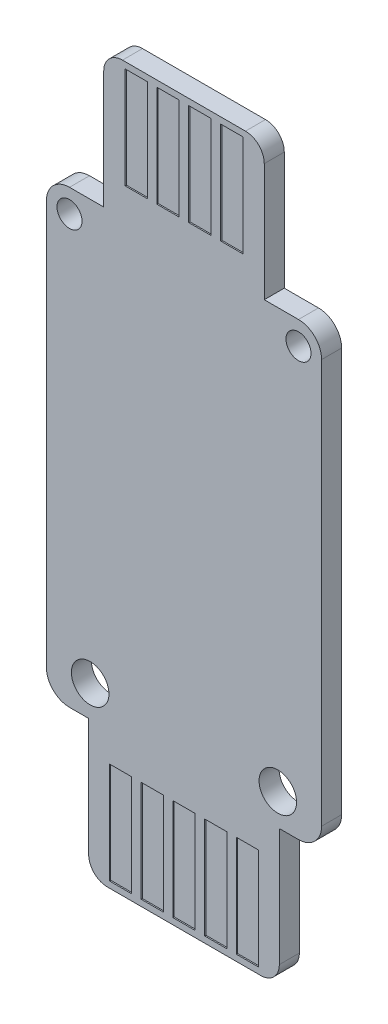
SolidWorks part; units mm, degrees
ref_plane "前视基准面" through (0, 0, 0) normal (0, 0, 1) x (1, 0, 0)
ref_plane "上视基准面" through (0, 0, 0) normal (0, 1, 0) x (1, 0, 0)
ref_plane "右视基准面" through (0, 0, 0) normal (1, 0, 0) x (0, 0, -1)
other "Configuration Table"
sketch "草图1" plane through (0, 0, 0) normal (0, 0, 1) x (1, 0, 0)
  line L1 (-9.15, 16) -> (9.15, 16)
  line L2 (-11, 14.15) -> (-11, -20)
  line L3 (-11, -20) -> (11, -20)
  line L4 (11, 14.15) -> (11, -20)
  arc A0 (-9.15, 16) -> (-11, 14.15) centre (-9.15, 14.15) ccw
  circle A1 centre (-9.15, 14.15) radius 1
  arc A2 (11, 14.15) -> (9.15, 16) centre (9.15, 14.15) ccw
  circle A3 centre (9.15, 14.15) radius 1
  point P0 (0, 0)
  point P6 (0, 0)
  dimension "D5" = 3.7
  dimension "D6" = 2
  dimension "D3" = 3.7
  dimension "D4" = 2
  dimension "D1" = 20
  dimension "D2" = 22
  dimension "D7" = 11
  dimension "D8" = 36
extrude "凸台-拉伸1" add sketch "草图1" along normal blind 1.6
sketch "草图3" plane through (0, 0, 0) normal (0, 0, 1) x (1, 0, 0)
  line L0 (-11, -20) -> (11, -20) construction
  line L1 (-10, -20) -> (10, -20) construction
  line L2 (-10, -20) -> (-10, 12) construction
  line L3 (-10, 12) -> (10, 12) construction
  line L4 (10, -20) -> (10, 12) construction
  line L5 (-11, 14.15) -> (-11, -20) construction
  circle A0 centre (-7.5, -17.5) radius 1.5
  circle A1 centre (7.5, -17.5) radius 1.5
  dimension "D4" = 3
  dimension "D7" = 3
  dimension "D1" = 32
  dimension "D2" = 20
  dimension "D3" = 1
  dimension "D5" = 2.5
  dimension "D6" = 2.5
  dimension "D8" = 2.5
  dimension "D9" = 2.5
extrude "切除-拉伸1" cut sketch "草图3" along normal blind 1.6
sketch "草图5" plane through (0, 0, 0) normal (0, 0, 1) x (1, 0, 0)
  line L0 (11, -20) -> (11, 14.15) construction
  line L1 (-11, -20) -> (11, -20) construction
  line L2 (-11, 14.15) -> (-11, -20) construction
  line L3 (11, -20) -> (11, -18.15)
  line L4 (-11, -20) -> (-9.15, -20)
  line L5 (-11, -18.15) -> (-11, -20)
  line L6 (9.15, -20) -> (11, -20)
  arc A0 (-11, -18.15) -> (-9.15, -20) centre (-9.15, -18.15) ccw
  arc A1 (9.15, -20) -> (11, -18.15) centre (9.15, -18.15) ccw
  dimension "D1" = 3.7
  dimension "D2" = 3.7
extrude "切除-拉伸2" cut sketch "草图5" along normal up to surface (1.6 mm away) up to face at (-6, -17.5, 1.6)
sketch "草图7" plane through (0, 0, 0) normal (0, 0, 1) x (1, 0, 0)
  line L0 (9.15, 16) -> (-9.15, 16) construction
  line L1 (-4.915, 26.92) -> (4.915, 26.92)
  line L2 (-6.415, 25.42) -> (-6.415, 16)
  line L3 (-6.415, 16) -> (6.415, 16)
  line L4 (6.415, 25.42) -> (6.415, 16)
  line L5 (-9.15, -20) -> (9.15, -20) construction
  line L6 (-6.415, -20) -> (6.415, -20)
  line L7 (-6.415, -20) -> (-6.415, -29.42)
  line L8 (-4.915, -30.92) -> (4.915, -30.92)
  line L9 (6.415, -20) -> (6.415, -29.42)
  arc A0 (-4.915, 26.92) -> (-6.415, 25.42) centre (-4.915, 25.42) ccw
  arc A1 (6.415, 25.42) -> (4.915, 26.92) centre (4.915, 25.42) ccw
  arc A2 (-6.415, -29.42) -> (-4.915, -30.92) centre (-4.915, -29.42) ccw
  arc A3 (4.915, -30.92) -> (6.415, -29.42) centre (4.915, -29.42) ccw
  point P6 (0, 16)
  point P7 (0, 16)
  point P19 (0, -20)
  point P20 (0, -20)
  dimension "D3" = 3
  dimension "D4" = 3
  dimension "D7" = 3
  dimension "D8" = 3
  dimension "D1" = 12.83
  dimension "D2" = 10.92
  dimension "D5" = 10.92
  dimension "D6" = 12.83
extrude "凸台-拉伸2" add sketch "草图7" along normal up to surface (1.6 mm away) up to face at (-6, -17.5, 1.6)
sketch "草图8" plane through (0, 0, 0) normal (0, 0, 1) x (1, 0, 0)
  line L0 (4.915, 26.92) -> (-4.915, 26.92) construction
  line L1 (-2.16, 26.42) -> (-0.38, 26.42)
  line L2 (-2.16, 26.42) -> (-2.16, 18.32)
  line L3 (-2.16, 18.32) -> (-0.38, 18.32)
  line L4 (-0.38, 26.42) -> (-0.38, 18.32)
  line L5 (0, -1000) -> (0, 49000) construction
  line L6 (0, -30.92) -> (0, 26.92) construction
  line L7 (-4.915, -30.92) -> (4.915, -30.92) construction
  line L8 (-1000, -2) -> (49000, -2) construction
  line L9 (-4.7, 26.42) -> (-2.92, 26.42)
  line L10 (-4.7, 26.42) -> (-4.7, 18.32)
  line L11 (-4.7, 18.32) -> (-2.92, 18.32)
  line L12 (-2.92, 26.42) -> (-2.92, 18.32)
  line L13 (-2.16, 26.42) -> (-4.7, 26.42) construction
  line L14 (2.16, 26.42) -> (4.7, 26.42) construction
  line L15 (2.92, 26.42) -> (2.92, 18.32)
  line L16 (4.7, 18.32) -> (2.92, 18.32)
  line L17 (4.7, 26.42) -> (4.7, 18.32)
  line L18 (4.7, 26.42) -> (2.92, 26.42)
  line L19 (0.38, 26.42) -> (0.38, 18.32)
  line L20 (2.16, 18.32) -> (0.38, 18.32)
  line L21 (2.16, 26.42) -> (2.16, 18.32)
  line L22 (2.16, 26.42) -> (0.38, 26.42)
  line L23 (2.16, -30.42) -> (4.7, -30.42) construction
  line L24 (-2.16, -30.42) -> (-4.7, -30.42) construction
  line L25 (0, 996) -> (0, -49004) construction
  line L26 (2.16, -30.42) -> (0.38, -30.42)
  line L27 (2.16, -30.42) -> (2.16, -22.32)
  line L28 (2.16, -22.32) -> (0.38, -22.32)
  line L29 (0.38, -30.42) -> (0.38, -22.32)
  line L30 (4.7, -30.42) -> (2.92, -30.42)
  line L31 (4.7, -30.42) -> (4.7, -22.32)
  line L32 (4.7, -22.32) -> (2.92, -22.32)
  line L33 (2.92, -30.42) -> (2.92, -22.32)
  line L34 (-2.92, -30.42) -> (-2.92, -22.32)
  line L35 (-4.7, -22.32) -> (-2.92, -22.32)
  line L36 (-4.7, -30.42) -> (-4.7, -22.32)
  line L37 (-4.7, -30.42) -> (-2.92, -30.42)
  line L38 (-0.38, -30.42) -> (-0.38, -22.32)
  line L39 (-2.16, -22.32) -> (-0.38, -22.32)
  line L40 (-2.16, -30.42) -> (-2.16, -22.32)
  line L41 (-2.16, -30.42) -> (-0.38, -30.42)
  point P16 (0, -2)
  dimension "D1" = 1.78
  dimension "D2" = 8.1
  dimension "D3" = 0.5
  dimension "D4" = 0.38
  dimension "D5" = 2
  dimension "D6" = 2.54
extrude "切除-拉伸3" cut sketch "草图8" along normal blind 0.1
sketch "草图9" plane through (0, 0, 0) normal (0, 0, 1) x (1, 0, 0)
  line L4 (-0.38, 26.42) -> (-2.16, 26.42)
  line L5 (-0.38, 18.32) -> (-0.38, 26.42)
  line L6 (-2.16, 18.32) -> (-0.38, 18.32)
  line L7 (-2.16, 26.42) -> (-2.16, 18.32)
  line L8 (-0.38, 26.42) -> (-2.16, 26.42)
  line L9 (-0.38, 18.32) -> (-0.38, 26.42)
  line L10 (-2.16, 18.32) -> (-0.38, 18.32)
  line L11 (-2.16, 26.42) -> (-2.16, 18.32)
  line L12 (0.38, 26.42) -> (0.38, 18.32)
  line L13 (0.38, 18.32) -> (2.16, 18.32)
  line L14 (2.16, 18.32) -> (2.16, 26.42)
  line L15 (2.16, 26.42) -> (0.38, 26.42)
  line L16 (0.38, 26.42) -> (0.38, 18.32)
  line L17 (0.38, 18.32) -> (2.16, 18.32)
  line L18 (2.16, 18.32) -> (2.16, 26.42)
  line L19 (2.16, 26.42) -> (0.38, 26.42)
  line L20 (2.92, 26.42) -> (2.92, 18.32)
  line L21 (2.92, 18.32) -> (4.7, 18.32)
  line L22 (4.7, 18.32) -> (4.7, 26.42)
  line L23 (4.7, 26.42) -> (2.92, 26.42)
  line L24 (2.92, 26.42) -> (2.92, 18.32)
  line L25 (2.92, 18.32) -> (4.7, 18.32)
  line L26 (4.7, 18.32) -> (4.7, 26.42)
  line L27 (4.7, 26.42) -> (2.92, 26.42)
  line L28 (-2.92, 26.42) -> (-4.7, 26.42)
  line L29 (-2.92, 18.32) -> (-2.92, 26.42)
  line L30 (-4.7, 18.32) -> (-2.92, 18.32)
  line L31 (-4.7, 26.42) -> (-4.7, 18.32)
  line L32 (-2.92, 26.42) -> (-4.7, 26.42)
  line L33 (-2.92, 18.32) -> (-2.92, 26.42)
  line L34 (-4.7, 18.32) -> (-2.92, 18.32)
  line L35 (-4.7, 26.42) -> (-4.7, 18.32)
  line L36 (-0.38, -30.42) -> (-0.38, -22.32)
  line L37 (-0.38, -22.32) -> (-2.16, -22.32)
  line L38 (-2.16, -22.32) -> (-2.16, -30.42)
  line L39 (-2.16, -30.42) -> (-0.38, -30.42)
  line L40 (-0.38, -30.42) -> (-0.38, -22.32)
  line L41 (-0.38, -22.32) -> (-2.16, -22.32)
  line L42 (-2.16, -22.32) -> (-2.16, -30.42)
  line L43 (-2.16, -30.42) -> (-0.38, -30.42)
  line L44 (-2.92, -30.42) -> (-2.92, -22.32)
  line L45 (-2.92, -22.32) -> (-4.7, -22.32)
  line L46 (-4.7, -22.32) -> (-4.7, -30.42)
  line L47 (-4.7, -30.42) -> (-2.92, -30.42)
  line L48 (-2.92, -30.42) -> (-2.92, -22.32)
  line L49 (-2.92, -22.32) -> (-4.7, -22.32)
  line L50 (-4.7, -22.32) -> (-4.7, -30.42)
  line L51 (-4.7, -30.42) -> (-2.92, -30.42)
  line L52 (2.92, -30.42) -> (4.7, -30.42)
  line L53 (4.7, -30.42) -> (4.7, -22.32)
  line L54 (4.7, -22.32) -> (2.92, -22.32)
  line L55 (2.92, -22.32) -> (2.92, -30.42)
  line L56 (2.92, -30.42) -> (4.7, -30.42)
  line L57 (4.7, -30.42) -> (4.7, -22.32)
  line L58 (4.7, -22.32) -> (2.92, -22.32)
  line L59 (2.92, -22.32) -> (2.92, -30.42)
  line L60 (0.38, -30.42) -> (2.16, -30.42)
  line L61 (2.16, -30.42) -> (2.16, -22.32)
  line L62 (2.16, -22.32) -> (0.38, -22.32)
  line L63 (0.38, -22.32) -> (0.38, -30.42)
  line L64 (0.38, -30.42) -> (2.16, -30.42)
  line L65 (2.16, -30.42) -> (2.16, -22.32)
  line L66 (2.16, -22.32) -> (0.38, -22.32)
  line L67 (0.38, -22.32) -> (0.38, -30.42)
  dimension "D1" = 0
  dimension "D2" = 0
  dimension "D3" = 0
  dimension "D4" = 0
  dimension "D5" = 0
  dimension "D6" = 0
  dimension "D7" = 0
  dimension "D8" = 0
extrude "切除-拉伸4" cut sketch "草图9" against normal blind 0.1 from surface at 1.6 starting at face at (-6, -17.5, 1.6)
sketch "草图11" plane through (0, 0, 0) normal (0, 0, 1) x (1, 0, 0)
  line L0 (6.415, -20) -> (9.15, -20) construction
  line L1 (-7.62, -20) -> (7.62, -20)
  line L2 (-7.62, -20) -> (-7.62, -29.42)
  line L3 (-6.12, -30.92) -> (6.12, -30.92)
  line L4 (7.62, -20) -> (7.62, -29.42)
  line L5 (-4.915, -30.92) -> (4.915, -30.92) construction
  arc A0 (-7.62, -29.42) -> (-6.12, -30.92) centre (-6.12, -29.42) ccw
  arc A1 (6.12, -30.92) -> (7.62, -29.42) centre (6.12, -29.42) ccw
  point P8 (0, -20)
  dimension "D4" = 3
  dimension "D5" = 3
  dimension "D1" = 0
  dimension "D2" = 0
  dimension "D3" = 15.24
extrude "凸台-拉伸3" add sketch "草图11" along normal up to surface (1.6 mm away) from surface at 0 up to face at (-6, -17.5, 1.6) starting at face at (3.81, 22.37, 0)
sketch "草图12" plane through (0, 0, 0) normal (0, 0, 1) x (1, 0, 0)
  line L0 (1.65, -22.32) -> (1.65, -30.42)
  line L1 (1.65, -22.32) -> (3.43, -22.32)
  line L2 (-6.12, -30.92) -> (6.12, -30.92) construction
  line L3 (-0.89, -22.32) -> (0.89, -22.32)
  line L4 (-0.89, -22.32) -> (-0.89, -30.42)
  line L5 (-0.89, -30.42) -> (0.89, -30.42)
  line L6 (0.89, -22.32) -> (0.89, -30.42)
  line L7 (3.43, -22.32) -> (3.43, -30.42)
  line L8 (1.65, -30.42) -> (3.43, -30.42)
  line L9 (4.19, -22.32) -> (4.19, -30.42)
  line L10 (4.19, -22.32) -> (5.97, -22.32)
  line L11 (5.97, -22.32) -> (5.97, -30.42)
  line L12 (4.19, -30.42) -> (5.97, -30.42)
  line L13 (-0.89, -22.32) -> (1.65, -22.32) construction
  line L14 (-3.43, -22.32) -> (-1.65, -22.32)
  line L15 (-3.43, -22.32) -> (-3.43, -30.42)
  line L16 (-3.43, -30.42) -> (-1.65, -30.42)
  line L17 (-1.65, -22.32) -> (-1.65, -30.42)
  line L18 (-5.97, -22.32) -> (-4.19, -22.32)
  line L19 (-5.97, -22.32) -> (-5.97, -30.42)
  line L20 (-5.97, -30.42) -> (-4.19, -30.42)
  line L21 (-4.19, -22.32) -> (-4.19, -30.42)
  line L22 (-0.89, -22.32) -> (-3.43, -22.32) construction
  point P2 (0, -22.32)
  dimension "D1" = 8.1
  dimension "D2" = 1.78
  dimension "D3" = 0.5
  dimension "D5" = 2.54
  dimension "D7" = 2.54
  dimension "D4" = 3
  dimension "D6" = 3
extrude "切除-拉伸5" cut sketch "草图12" along normal blind 0.1 from surface at 0 starting at face at (3.81, 22.37, 0)
sketch "草图13" plane through (0, 0, 0) normal (0, 0, 1) x (1, 0, 0)
  line L4 (0.89, -22.32) -> (-0.89, -22.32)
  line L5 (0.89, -30.42) -> (0.89, -22.32)
  line L6 (-0.89, -30.42) -> (0.89, -30.42)
  line L7 (-0.89, -22.32) -> (-0.89, -30.42)
  line L8 (0.89, -22.32) -> (-0.89, -22.32)
  line L9 (0.89, -30.42) -> (0.89, -22.32)
  line L10 (-0.89, -30.42) -> (0.89, -30.42)
  line L11 (-0.89, -22.32) -> (-0.89, -30.42)
  line L12 (1.65, -22.32) -> (1.65, -30.42)
  line L13 (1.65, -30.42) -> (3.43, -30.42)
  line L14 (3.43, -30.42) -> (3.43, -22.32)
  line L15 (3.43, -22.32) -> (1.65, -22.32)
  line L16 (1.65, -22.32) -> (1.65, -30.42)
  line L17 (1.65, -30.42) -> (3.43, -30.42)
  line L18 (3.43, -30.42) -> (3.43, -22.32)
  line L19 (3.43, -22.32) -> (1.65, -22.32)
  line L20 (-4.19, -22.32) -> (-5.97, -22.32)
  line L21 (-4.19, -30.42) -> (-4.19, -22.32)
  line L22 (-5.97, -30.42) -> (-4.19, -30.42)
  line L23 (-5.97, -22.32) -> (-5.97, -30.42)
  line L24 (-4.19, -22.32) -> (-5.97, -22.32)
  line L25 (-4.19, -30.42) -> (-4.19, -22.32)
  line L26 (-5.97, -30.42) -> (-4.19, -30.42)
  line L27 (-5.97, -22.32) -> (-5.97, -30.42)
  line L28 (-1.65, -22.32) -> (-3.43, -22.32)
  line L29 (-3.43, -22.32) -> (-3.43, -30.42)
  line L30 (-3.43, -30.42) -> (-1.65, -30.42)
  line L31 (-1.65, -30.42) -> (-1.65, -22.32)
  line L32 (-1.65, -22.32) -> (-3.43, -22.32)
  line L33 (-3.43, -22.32) -> (-3.43, -30.42)
  line L34 (-3.43, -30.42) -> (-1.65, -30.42)
  line L35 (-1.65, -30.42) -> (-1.65, -22.32)
  line L36 (4.19, -22.32) -> (4.19, -30.42)
  line L37 (5.97, -22.32) -> (4.19, -22.32)
  line L38 (5.97, -30.42) -> (5.97, -22.32)
  line L39 (4.19, -30.42) -> (5.97, -30.42)
  line L40 (4.19, -22.32) -> (4.19, -30.42)
  line L41 (5.97, -22.32) -> (4.19, -22.32)
  line L42 (5.97, -30.42) -> (5.97, -22.32)
  line L43 (4.19, -30.42) -> (5.97, -30.42)
  dimension "D1" = 0
  dimension "D2" = 0
  dimension "D3" = 0
  dimension "D4" = 0
  dimension "D5" = 0
extrude "切除-拉伸6" cut sketch "草图13" against normal blind 0.1 from surface at 1.6 starting at face at (0, -2, 1.6)
